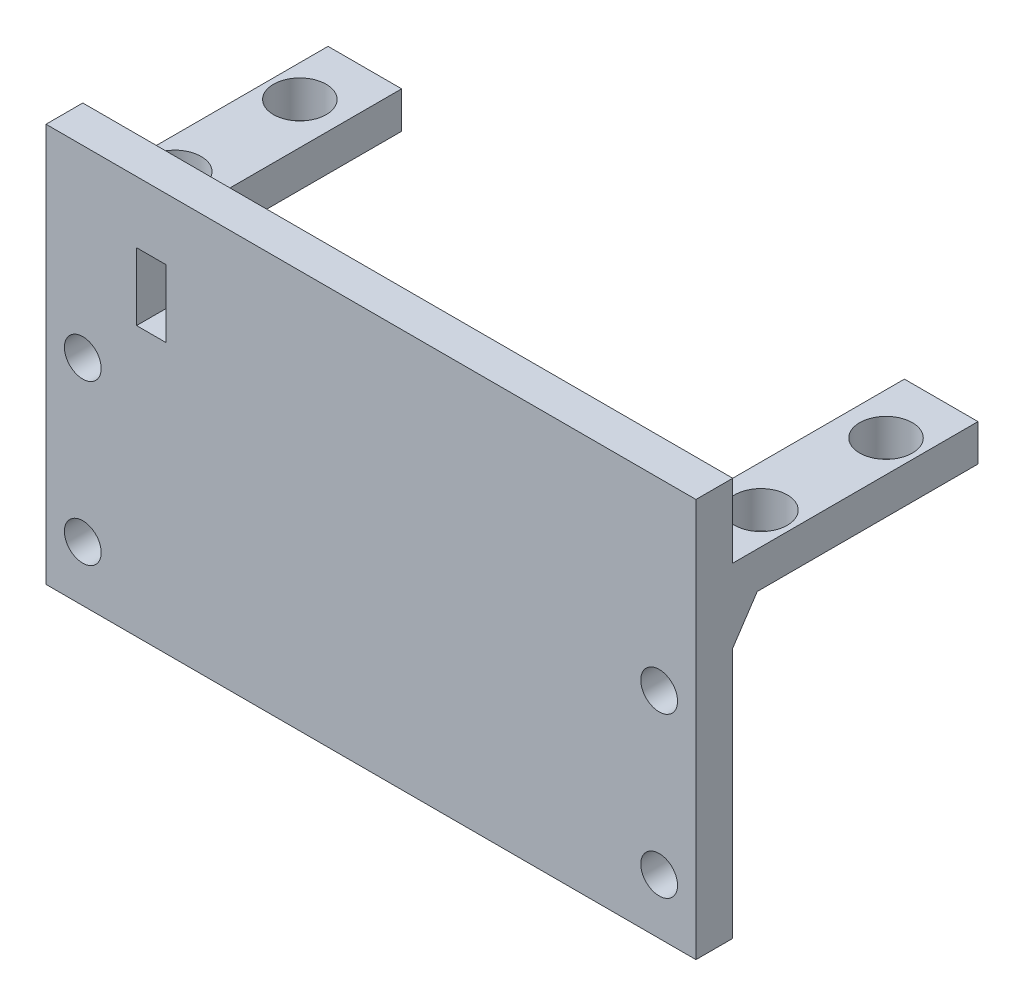
SolidWorks part; units mm, degrees
ref_plane "Front Plane" through (0, 0, 0) normal (0, 0, 1) x (1, 0, 0)
ref_plane "Top Plane" through (0, 0, 0) normal (0, 1, 0) x (1, 0, 0)
ref_plane "Right Plane" through (0, 0, 0) normal (1, 0, 0) x (0, 0, -1)
sketch "Sketch1" plane through (0, 0, 0) normal (0, 0, 1) x (1, 0, 0)
  line L0 (-16.7597, 16.0603) -> (-16.7597, 13.5603) construction
  line L1 (-16.7597, 19.5603) -> (36.2403, 19.5603)
  line L2 (-16.7597, 19.5603) -> (-16.7597, -12.9397)
  line L3 (-16.7597, -12.9397) -> (36.2403, -12.9397)
  line L4 (36.2403, 19.5603) -> (36.2403, -12.9397)
  line L5 (36.2403, 16.0603) -> (36.2403, 13.5603) construction
  line L6 (-8.2597, 19.5603) -> (27.7403, 19.5603) construction
  line L7 (25.4903, -12.9397) -> (-6.0097, -12.9397) construction
extrude "Boss-Extrude1" add sketch "Sketch1" along normal blind 3
sketch "Sketch5" plane through (0, 0, 0) normal (0, 0, -1) x (-1, 0, 0)
  line L0 (-36.2403, -12.9397) -> (-36.2403, 19.5603) construction
  line L1 (-36.2403, 10.5603) -> (-30.2403, 10.5603)
  line L2 (-36.2403, 10.5603) -> (-36.2403, 13.5603)
  line L3 (-36.2403, 13.5603) -> (-30.2403, 13.5603)
  line L4 (-30.2403, 10.5603) -> (-30.2403, 13.5603)
  line L5 (-29.0632, 13.5603) -> (-34.4287, 13.5603) construction
  line L6 (16.7597, 19.5603) -> (16.7597, -12.9397) construction
  line L7 (16.7597, 13.5603) -> (10.7597, 13.5603)
  line L8 (16.7597, 13.5603) -> (16.7597, 10.5603)
  line L9 (16.7597, 10.5603) -> (10.7597, 10.5603)
  line L10 (10.7597, 13.5603) -> (10.7597, 10.5603)
  line L11 (9.5825, 13.5603) -> (14.9481, 13.5603) construction
  dimension "D1" = 3
  dimension "D2" = 6
  dimension "D3" = 6
  dimension "D4" = 3
extrude "Boss-Extrude2" add sketch "Sketch5" along normal blind 20
sketch "Sketch6" plane through (0, 13.5603, 0) normal (0, 1, 0) x (1, 0, 0)
  line L0 (30.2403, 0) -> (36.2403, 0) construction
  line L1 (30.2403, 20) -> (30.2403, 0) construction
  circle A0 centre (33.6403, 4.9) radius 2.15
  circle A1 centre (33.6403, 15.1) radius 2.15
  circle A2 centre (-14.1597, 4.9) radius 2.15
  circle A3 centre (-14.1597, 15.1) radius 2.15
  dimension "D1" = 4.3
  dimension "D2" = 4.3
  dimension "D3" = 4.3
  dimension "D4" = 4.3
  dimension "D5" = 4.9
  dimension "D6" = 3.4
  dimension "D7" = 10.2
  dimension "D8" = 47.8
  dimension "D9" = 10.2
extrude "Cut-Extrude3" cut sketch "Sketch6" against normal blind 10
sketch "Sketch7" plane through (0, 0, 0) normal (0, 0, -1) x (-1, 0, 0)
  line L1 (9.3728, 14.5335) -> (9.3728, 9.0335)
  line L3 (-36.2403, 19.5603) -> (16.7597, 19.5603) construction
  line L5 (16.7597, 19.5603) -> (16.7597, -12.9397) construction
  line L16 (9.3728, 9.0335) -> (6.9728, 9.0335)
  line L17 (6.9728, 9.0335) -> (6.9728, 14.5335)
  line L18 (6.9728, 14.5335) -> (9.3728, 14.5335)
  dimension "D1" = 5.0268
  dimension "D2" = 5.5
  dimension "D3" = 7.3869
  dimension "D4" = 2.4
extrude "Cut-Extrude6" cut sketch "Sketch7" against normal blind 10 contours L18 L1 L16 L17
sketch "Sketch8" plane through (0, 0, 0) normal (0, 0, -1) x (-1, 0, 0)
  line L0 (16.7597, 19.5603) -> (16.7597, -12.9397) construction
  line L1 (-36.2403, 19.5603) -> (16.7597, 19.5603) construction
  line L2 (-36.2403, -12.9397) -> (-36.2403, 19.5603) construction
  circle A0 centre (-33.2403, 4.5603) radius 1.5
  circle A1 centre (-33.2403, -8.4397) radius 1.5
  circle A2 centre (13.7597, -8.4397) radius 1.5
  circle A3 centre (13.7597, 4.5603) radius 1.5
  dimension "D1" = 3
  dimension "D2" = 3
  dimension "D3" = 3
  dimension "D4" = 3
  dimension "D5" = 3
  dimension "D6" = 15
  dimension "D7" = 13
  dimension "D8" = 3
  dimension "D9" = 15
  dimension "D10" = 13
extrude "Cut-Extrude7" cut sketch "Sketch8" against normal blind 10
sketch "Sketch9" plane through (-16.7597, 0, 0) normal (-1, 0, 0) x (0, 0, 1)
  line L0 (-2, 10.5603) -> (0, 10.5603)
  line L1 (-20, 10.5603) -> (0, 10.5603) construction
  line L2 (0, 10.5603) -> (0, 7.5603)
  line L3 (0, 10.5603) -> (0, -12.9397) construction
  line L4 (0, 7.5603) -> (-2, 10.5603)
  point P5 (0, 7.3427)
  point P9 (0, 7.5411)
  point P10 (-2.1699, 10.5603)
  point P11 (0, 0)
  point P12 (0, 0)
  point P13 (0, 0)
  point P14 (0, 0)
  dimension "D1" = 2
  dimension "D2" = 3
extrude "Boss-Extrude3" add sketch "Sketch9" against normal up to surface (6 mm away) up to face at (-10.7597, 12.0603, -10)
sketch "Sketch10" plane through (36.2403, 0, 0) normal (1, 0, 0) x (0, 0, -1)
  line L0 (2, 10.5603) -> (0, 10.5603)
  line L1 (20, 10.5603) -> (0, 10.5603) construction
  line L2 (0, 10.5603) -> (0, 7.5603)
  line L3 (0, -12.9397) -> (0, 10.5603) construction
  line L4 (0, 7.5603) -> (2, 10.5603)
  dimension "D1" = 2
  dimension "D2" = 3
extrude "Boss-Extrude4" add sketch "Sketch10" against normal up to surface (6 mm away) up to face at (30.2403, 12.0603, -10)
